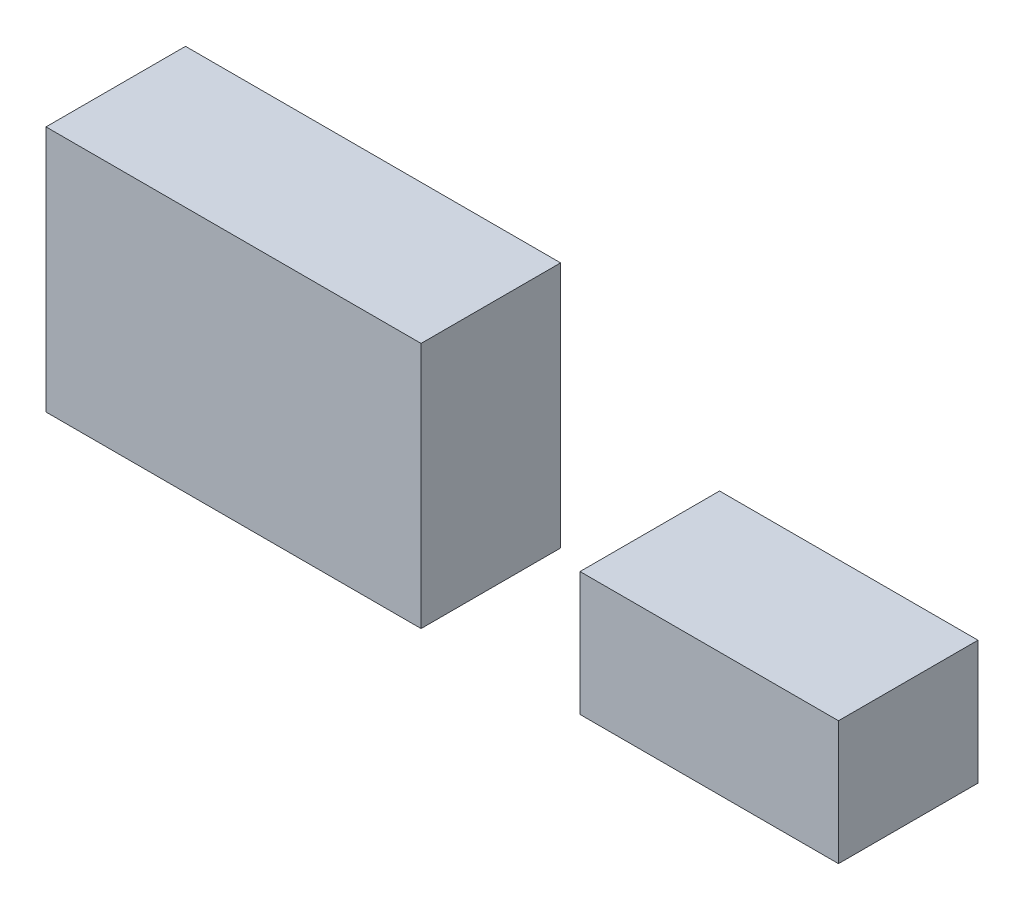
SolidWorks part; units mm, degrees
ref_plane "前视基准面" through (0, 0, 0) normal (0, 0, 1) x (1, 0, 0)
ref_plane "上视基准面" through (0, 0, 0) normal (0, 1, 0) x (1, 0, 0)
ref_plane "右视基准面" through (0, 0, 0) normal (1, 0, 0) x (0, 0, -1)
sketch "草图1" plane through (0, 0, 0) normal (0, 0, 1) x (1, 0, 0)
  line L1 (-141.4435, 75.7104) -> (25.2368, 75.7104)
  line L2 (-141.4435, 75.7104) -> (-141.4435, -34.0403)
  line L3 (-141.4435, -34.0403) -> (25.2368, -34.0403)
  line L4 (25.2368, 75.7104) -> (25.2368, -34.0403)
extrude "凸台-拉伸1" add sketch "草图1" along normal blind 62
sketch "草图2" plane through (0, 0, 0) normal (0, 0, 1) x (1, 0, 0)
  line L1 (95.8767, 23.2415) -> (210.7299, 23.2415)
  line L2 (95.8767, 23.2415) -> (95.8767, -31.7709)
  line L3 (95.8767, -31.7709) -> (210.7299, -31.7709)
  line L4 (210.7299, 23.2415) -> (210.7299, -31.7709)
extrude "凸台-拉伸2" add sketch "草图2" along normal blind 62 separate body
